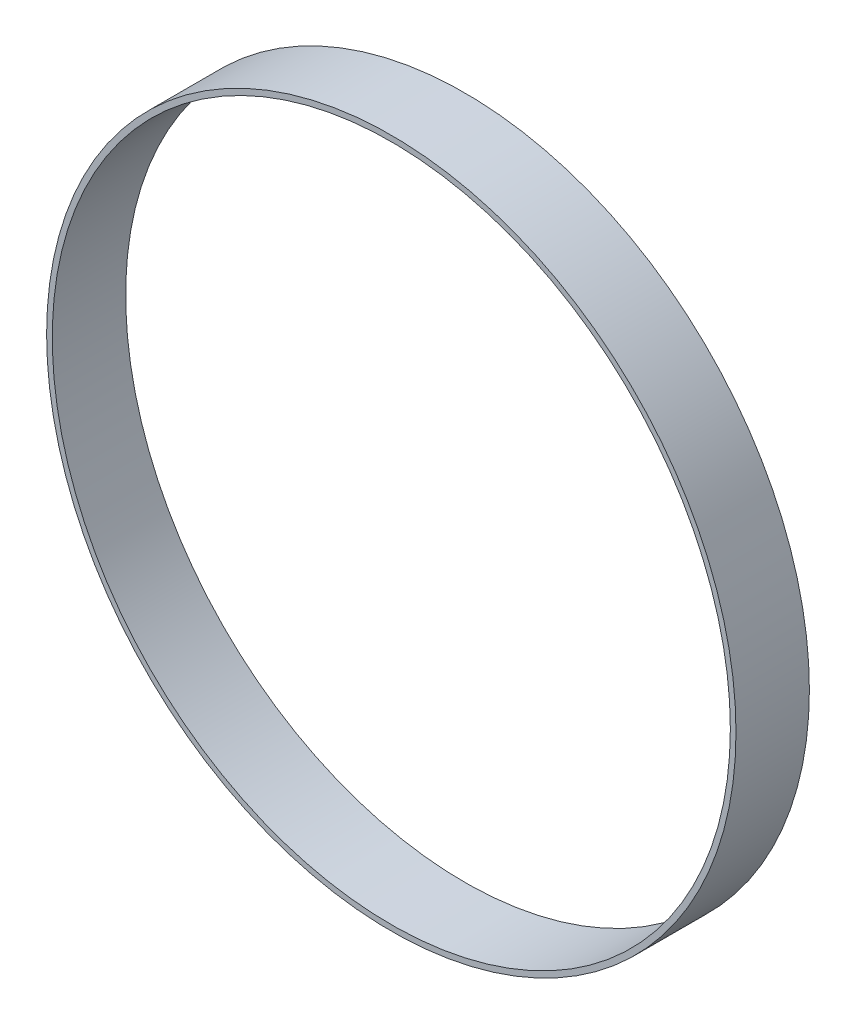
SolidWorks part; units mm, degrees
material "Malleable Cast Iron"
ref_plane "Front" through (0, 0, 0) normal (0, 0, 1) x (1, 0, 0)
ref_plane "Top" through (0, 0, 0) normal (0, 1, 0) x (1, 0, 0)
ref_plane "Right" through (0, 0, 0) normal (1, 0, 0) x (0, 0, -1)
sketch "Sketch1" plane through (0, 0, 0) normal (0, 0, 1) x (1, 0, 0)
  circle A0 centre (0, 0) radius 762.635
  circle A1 centre (0, 0) radius 775.335
  dimension "D1" = 1525.27
  dimension "D2" = 1550.67
extrude "Boss-Extrude1" add sketch "Sketch1" along normal blind 165.1
